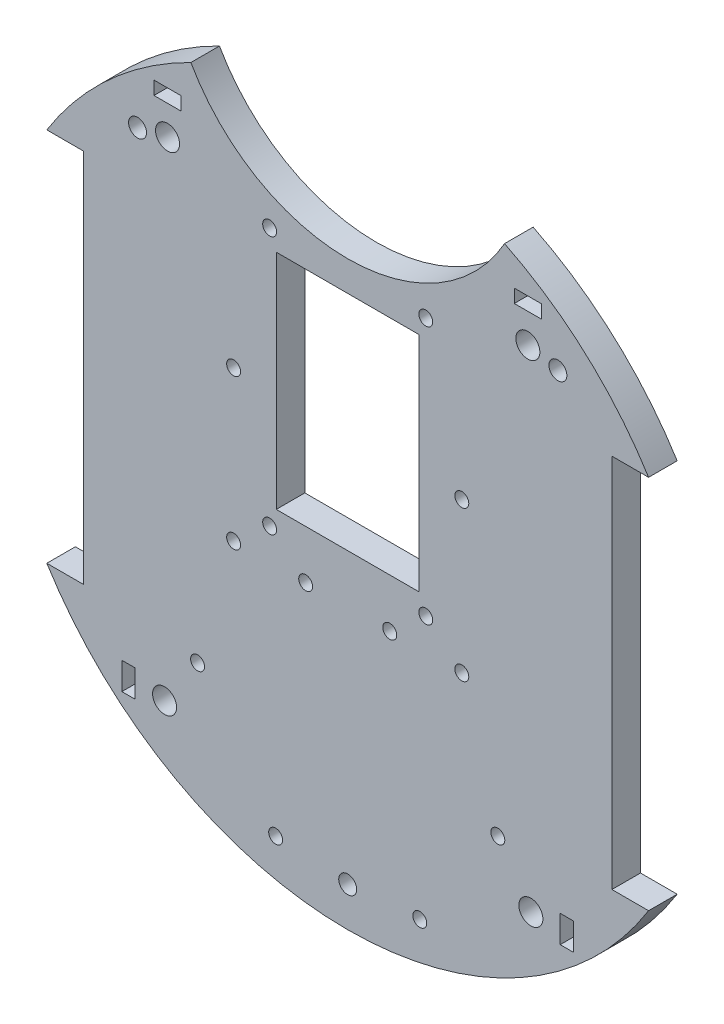
SolidWorks part; units mm, degrees
ref_plane "Front Plane" through (0, 0, 0) normal (0, 0, 1) x (1, 0, 0)
ref_plane "Top Plane" through (0, 0, 0) normal (0, 1, 0) x (1, 0, 0)
ref_plane "Right Plane" through (0, 0, 0) normal (1, 0, 0) x (0, 0, -1)
sketch "Sketch1" plane through (0, 0, 0) normal (0, 0, 1) x (1, 0, 0)
  line L0 (0, 47.9049) -> (0, -75) construction
  line L1 (-55.88, 0) -> (55.88, 0) construction
  line L2 (-63.6388, 39.6875) -> (-55.88, 39.6875)
  line L4 (-63.6388, -39.6875) -> (-55.88, -39.6875)
  line L5 (-55.88, 39.6875) -> (-55.88, -39.6875)
  line L22 (55.88, 39.6875) -> (55.88, -39.6875)
  line L23 (63.6388, -39.6875) -> (55.88, -39.6875)
  line L25 (63.6388, 39.6875) -> (55.88, 39.6875)
  arc A0 (-33.1727, 67.265) -> (-63.6388, 39.6875) centre (0, 0) ccw
  arc A1 (-33.1727, 67.265) -> (33.1727, 67.265) centre (0, 86.0049) ccw
  circle A2 centre (0, -66.675) radius 1.8987
  circle A3 centre (-44.45, 49.6966) radius 1.8987
  circle A4 centre (44.45, 49.6966) radius 1.8986
  circle A5 centre (-24.13, -15.875) radius 1.4732
  circle A6 centre (-8.89, -15.875) radius 1.4732
  circle A7 centre (8.89, -15.875) radius 1.4732
  circle A8 centre (-15.24, -65.475) radius 1.4732
  circle A9 centre (15.24, -65.475) radius 1.4732
  circle A12 centre (24.13, -15.875) radius 1.4732
  circle A13 centre (8.89, 15.875) radius 1.4732
  circle A14 centre (-8.89, 15.875) radius 1.4732
  circle A15 centre (24.13, 15.875) radius 1.4732
  circle A18 centre (-24.13, 15.875) radius 1.4732
  arc A29 (-63.6388, -39.6875) -> (63.6388, -39.6875) centre (0, 0) ccw
  arc A30 (63.6388, 39.6875) -> (33.1727, 67.265) centre (0, 0) ccw
  circle A31 centre (0, 0) radius 66.675 construction
  point P1 (-55.88, 0)
  point P50 (0, -65.475)
  dimension "D1" = 150
  dimension "D8" = 3.7973
  dimension "D12" = 133.35
  dimension "D11" = 3.7973
  dimension "D20" = 31.75
  dimension "D19" = 2.9464
  dimension "D9" = 2.9464
  dimension "D2" = 66.3453
  dimension "D3" = 38.1
  dimension "D4" = 44.45
  dimension "D5" = 79.375
  dimension "D6" = 55.88
  dimension "D7" = 0
  dimension "D13" = 15.875
  dimension "D14" = 9.525
  dimension "D18" = 0
  dimension "D23" = 15.24
  dimension "D10" = 15.24
extrude "Boss-Extrude3" add sketch "Sketch1" along normal blind 6.0452
sketch "Sketch7" plane through (0, 0, 6.0452) normal (0, 0, 1) x (1, 0, 0)
  line L0 (-34.925, -41.98) -> (34.925, -41.98) construction
  line L1 (-34.925, -61.03) -> (-34.925, -22.93) construction
  line L2 (-34.925, -61.03) -> (34.925, -61.03) construction
  line L3 (34.925, -61.03) -> (34.925, -22.93) construction
  line L4 (-34.925, -22.93) -> (34.925, -22.93) construction
  line L5 (0, -61.03) -> (0, -22.93) construction
  line L6 (-28.575, -55.7849) -> (-28.575, -28.1751) construction
  line L7 (-28.575, -55.7849) -> (28.575, -55.7849) construction
  line L8 (28.575, -55.7849) -> (28.575, -28.1751) construction
  line L9 (-28.575, -28.1751) -> (28.575, -28.1751) construction
  line L10 (-28.575, -55.7849) -> (28.575, -28.1751) construction
  line L11 (28.575, -55.7849) -> (-28.575, -28.1751) construction
  line L12 (0, 47.9049) -> (0, -75) construction
  circle A0 centre (-31.75, -41.98) radius 1.4732
  circle A1 centre (31.75, -41.98) radius 1.4732
  arc A2 (-33.1727, 67.265) -> (33.1727, 67.265) centre (0, 86.0049) ccw construction
  arc A3 (-63.6388, -39.6875) -> (63.6388, -39.6875) centre (0, 0) ccw construction
  point P0 (0, -41.98)
  dimension "D1" = 69.85
  dimension "D2" = 57.15
  dimension "D3" = 27.6098
  dimension "D4" = 3.175
  dimension "D5" = 38.1
  dimension "D6" = 33.02
extrude "Cut-Extrude2" cut sketch "Sketch7" against normal through all
sketch "Sketch9" plane through (0, 0, 6.0452) normal (0, 0, 1) x (1, 0, 0)
  line L1 (-15.113, 41.5549) -> (15.113, 41.5549)
  line L2 (-15.113, 41.5549) -> (-15.113, -5.5621)
  line L3 (-15.113, -5.5621) -> (15.113, -5.5621)
  line L4 (15.113, 41.5549) -> (15.113, -5.5621)
  line L5 (-15.113, 17.9964) -> (15.113, 17.9964) construction
  line L6 (0, 47.8414) -> (0, -11.8486) construction
  line L7 (0, 47.9049) -> (0, -75) construction
  line L8 (-19.05, 47.8414) -> (19.05, 47.8414) construction
  line L9 (-19.05, 47.8414) -> (-19.05, -11.8486) construction
  line L10 (-19.05, -11.8486) -> (19.05, -11.8486) construction
  line L11 (19.05, 47.8414) -> (19.05, -11.8486) construction
  line L12 (-19.05, 17.9964) -> (19.05, 17.9964) construction
  arc A1 (-33.1727, 67.265) -> (33.1727, 67.265) centre (0, 86.0049) ccw construction
  arc A2 (-63.6388, -39.6875) -> (63.6388, -39.6875) centre (0, 0) ccw construction
  circle A3 centre (-16.51, 45.3014) radius 1.4732
  circle A4 centre (16.51, 45.3014) radius 1.4732
  circle A5 centre (-16.51, -9.3086) radius 1.4732
  circle A6 centre (16.51, -9.3086) radius 1.4732
  point P6 (0, 17.9964)
  dimension "D6" = 2.9464
  dimension "D7" = 5.08
  dimension "D8" = 5.08
  dimension "D1" = 30.226
  dimension "D2" = 47.117
  dimension "D3" = 6.35
  dimension "D4" = 59.69
  dimension "D5" = 38.1
extrude "Cut-Extrude3" cut sketch "Sketch9" against normal blind 14.732
sketch "Sketch10" plane through (0, 0, 6.0452) normal (0, 0, 1) x (1, 0, 0)
  line L0 (0, 47.9049) -> (0, -75) construction
  line L1 (-63.6388, 39.6875) -> (-55.88, 39.6875) construction
  line L2 (-40.9702, 60.1472) -> (-35.2298, 60.1472)
  line L3 (-40.9702, 60.1472) -> (-40.9702, 57.3278)
  line L4 (-40.9702, 57.3278) -> (-35.2298, 57.3278)
  line L5 (-35.2298, 60.1472) -> (-35.2298, 57.3278)
  line L6 (-40.9702, 60.1472) -> (-35.2298, 57.3278) construction
  line L7 (-40.9702, 57.3278) -> (-35.2298, 60.1472) construction
  line L8 (35.2298, 60.1472) -> (35.2298, 57.3278)
  line L9 (40.9702, 60.1472) -> (35.2298, 60.1472)
  line L10 (40.9702, 60.1472) -> (40.9702, 57.3278)
  line L11 (40.9702, 57.3278) -> (35.2298, 57.3278)
  line L12 (-55.88, -39.6875) -> (-63.6388, -39.6875) construction
  line L13 (-47.7647, -49.5173) -> (-44.9453, -49.5173)
  line L14 (-47.7647, -49.5173) -> (-47.7647, -55.2577)
  line L15 (-47.7647, -55.2577) -> (-44.9453, -55.2577)
  line L16 (-44.9453, -49.5173) -> (-44.9453, -55.2577)
  line L17 (-47.7647, -49.5173) -> (-44.9453, -55.2577) construction
  line L18 (-47.7647, -55.2577) -> (-44.9453, -49.5173) construction
  line L19 (47.7647, -55.2577) -> (44.9453, -49.5173) construction
  line L20 (47.7647, -49.5173) -> (44.9453, -55.2577) construction
  line L21 (44.9453, -49.5173) -> (44.9453, -55.2577)
  line L22 (47.7647, -55.2577) -> (44.9453, -55.2577)
  line L23 (47.7647, -49.5173) -> (47.7647, -55.2577)
  line L24 (47.7647, -49.5173) -> (44.9453, -49.5173)
  arc A0 (-33.1727, 67.265) -> (33.1727, 67.265) centre (0, 86.0049) ccw construction
  arc A1 (-63.6388, -39.6875) -> (63.6388, -39.6875) centre (0, 0) ccw construction
  circle A3 centre (-38.735, -52.3875) radius 2.54
  circle A4 centre (38.735, -52.3875) radius 2.54
  circle A5 centre (-38.1, 51.1175) radius 2.54
  circle A6 centre (38.1, 51.1175) radius 2.54
  point P8 (-38.1, 58.7375)
  point P19 (-46.355, -52.3875)
  point P30 (46.355, -52.3875)
  dimension "D8" = 5.08
  dimension "D10" = 5.08
  dimension "D1" = 2.8194
  dimension "D2" = 5.7404
  dimension "D3" = 38.1
  dimension "D4" = 19.05
  dimension "D5" = 46.355
  dimension "D6" = 12.7
  dimension "D7" = 7.62
  dimension "D9" = 7.62
extrude "Cut-Extrude4" cut sketch "Sketch10" against normal up to surface (6.0452 mm away) up to face at (17.9832, -9.3086, 0)
